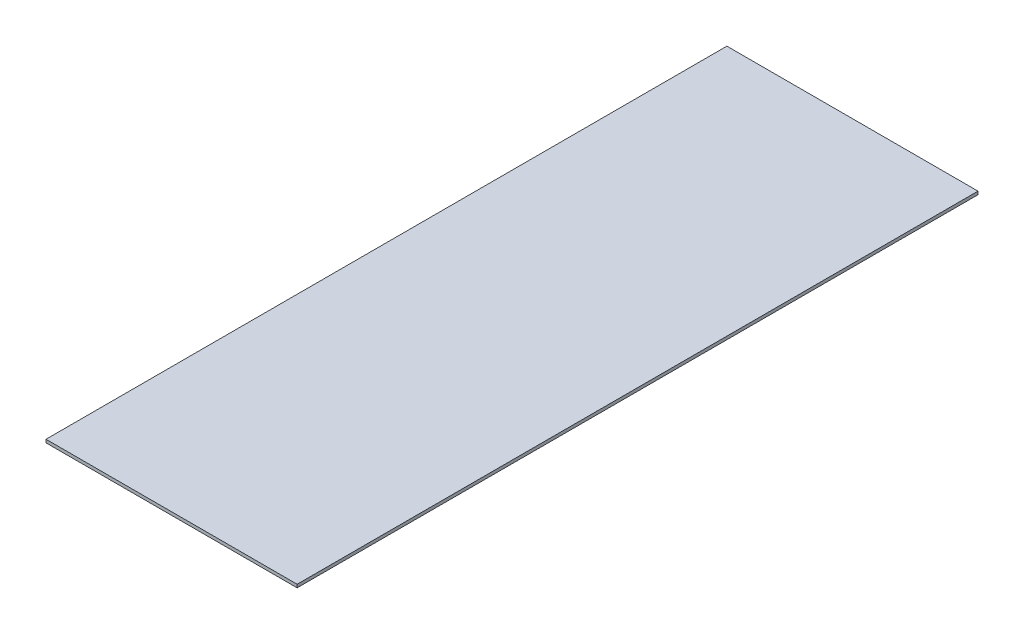
SolidWorks part; units mm, degrees
ref_plane "Front Plane" through (0, 0, 0) normal (0, 0, 1) x (1, 0, 0)
ref_plane "Top Plane" through (0, 0, 0) normal (0, 1, 0) x (1, 0, 0)
ref_plane "Right Plane" through (0, 0, 0) normal (1, 0, 0) x (0, 0, -1)
sketch "Sketch1" plane through (0, 0, 0) normal (0, 1, 0) x (1, 0, 0)
  line L1 (-30.3, 36.3099) -> (172.9, 36.3099)
  line L2 (-30.3, 36.3099) -> (-30.3, -514.6161)
  line L3 (-30.3, -514.6161) -> (172.9, -514.6161)
  line L4 (172.9, 36.3099) -> (172.9, -514.6161)
  dimension "D1" = 203.2
  dimension "D2" = 550.926
extrude "Boss-Extrude1" add sketch "Sketch1" along normal blind 2.54
